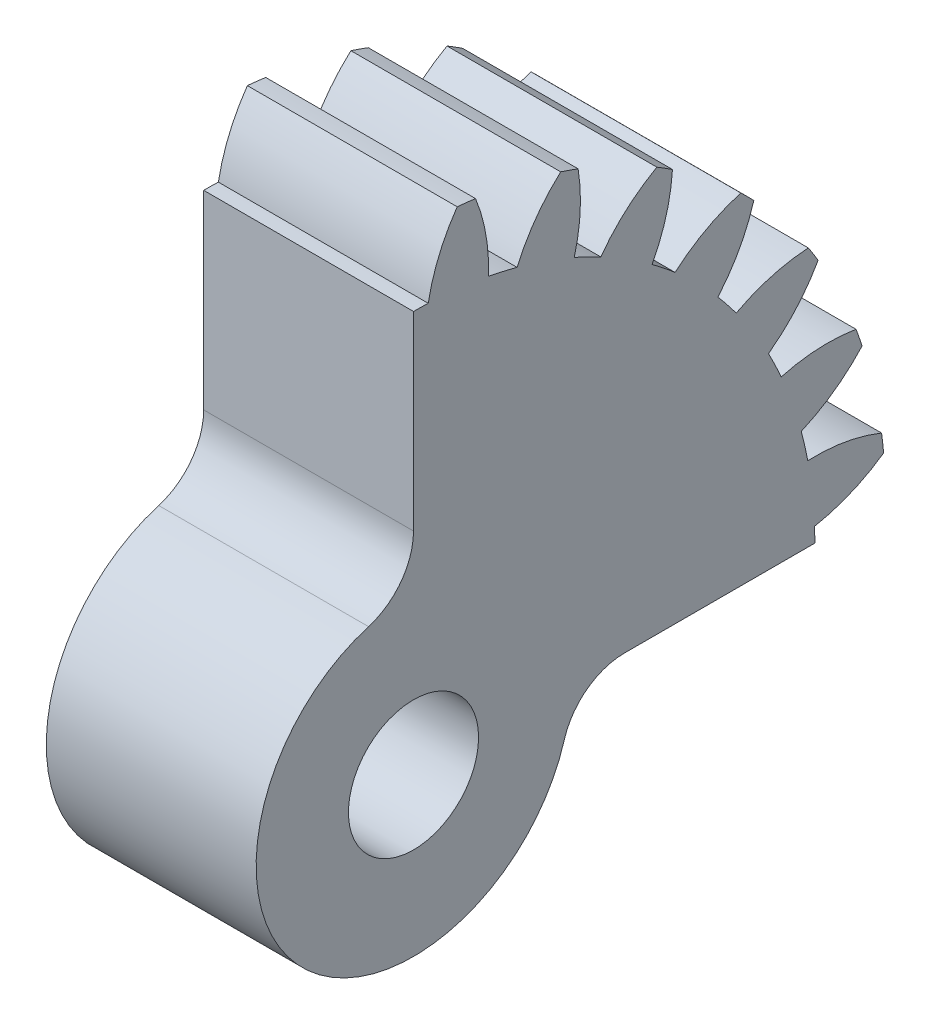
SolidWorks part; units mm, degrees
ref_plane "Plane1" through (0, 0, 0) normal (0, 0, 1) x (1, 0, 0)
ref_plane "Plane2" through (0, 0, 0) normal (0, 1, 0) x (1, 0, 0)
ref_plane "Plane3" through (0, 0, 0) normal (1, 0, 0) x (0, 0, -1)
sketch "HoldingSke" plane through (0, 0, 0) normal (0, 1, 0) x (1, 0, 0)
  line L0 (0, 0) -> (0.5886, -0.313)
  line L1 (-15, 0) -> (100, 0) construction
  line L2 (0, 0) -> (-2.1039, 2.3779)
  line L3 (0, 0) -> (-11.863, 4.5341)
  line L4 (0, 0) -> (7.6251, 4.0544)
  line L5 (0, 0) -> (-46.8476, -17.4728)
  line L6 (0, 0) -> (-8.2896, -5.593)
  line L7 (-2.1039, 2.3779) -> (8.6586, 51.2059)
  line L8 (-76.2, 54.61) -> (-73.9, 54.61)
  line L9 (-71.009, 38.7566) -> (-53.1078, 45.2721)
  line L10 (-76.2, 71.12) -> (104.1128, 71.12)
  line L11 (0, 0) -> (-10, 0)
  line L12 (-76.2, 101.6) -> (-76.147, 101.6)
  line L13 (24.9733, 27.94) -> (52.9518, 28.4284)
  line L14 (24.9733, 27.94) -> (24.9743, 27.94)
  line L15 (24.9733, 27.94) -> (100.4006, 29.5858)
  line L16 (-63.627, -1.5) -> (-12.827, -1.5)
  circle A0 centre (0, 0) radius 7.5
  circle A1 centre (0, 0) radius 19.124
  circle A2 centre (0, 0) radius 37.5
  circle A3 centre (0, 0) radius 7.5
  dimension "MHD" = 38.248
  dimension "Hub_dia" = 75
  dimension "Bore" = 15
  dimension "MBD" = 15
  dimension "Num_teeth" = 28
  dimension "Pitch_radius" = 180.3128
  dimension "Pitch" = 0.6667
  dimension "Width" = 10
  dimension "Overall_len" = 50
  dimension "Show_teeth" = 28
  dimension "Thickness" = 10
  dimension "OAL" = 50.0001
  dimension "T_dim" = 2.3
  dimension "Ap" = 20
  dimension "H" = 19.05
  dimension "Backlash" = 0.053
  dimension "Addendum_fac" = 1
  dimension "Dedendum_fac" = 1.25
  dimension "Clearance_fac" = 0.25
  dimension "Dedendum_add" = 0.001
  dimension "Module" = 1.5
sketch "BasProSke" plane through (0, 0, 0) normal (0, 1, 0) x (1, 0, 0)
  line L0 (-10, 0) -> (60, 0) construction
  line L1 (0, 0) -> (0, 22.5)
  line L2 (0, 0) -> (10, 0)
  line L3 (10, 0) -> (10, 22.5)
  line L4 (10, 22.5) -> (0, 22.5)
  dimension "Diameter" = 45
  dimension "Thickness" = 10
revolve "Base-Revolve" add sketch "BasProSke" angle 360 about L0
sketch "TooCutSke" plane through (0, 0, 0) normal (1, 0, 0) x (0, 0, -1)
  line L1 (0, 0) -> (0, 107) construction
  line L2 (0, 0) -> (-1.2702, 20.9615) construction
  line L3 (0, 0) -> (-4.6962, 41.6802) construction
  line L4 (-1.2702, 20.9615) -> (-2.3481, 20.8401) construction
  arc A0 (0.7007, 19.1112) -> (-0.7007, 19.1112) centre (0, 0) ccw
  arc A1 (2.0988, 22.4274) -> (-2.0988, 22.4274) centre (0, 0) ccw
  circle A2 centre (0, 0) radius 21 construction
  circle A3 centre (0, 0) radius 19.7335 construction
  arc A4 (-0.7007, 19.1112) -> (-2.0988, 22.4274) centre (-8.9603, 17.5819) ccw
  arc A5 (2.0988, 22.4274) -> (0.7007, 19.1112) centre (8.9603, 17.5819) ccw
  dimension "Root_dia" = 38.248
  dimension "Overcut_dia" = 45.0508
  dimension "Pitch_dia" = 42
  dimension "Base_dia" = 39.4671
  dimension "Flank_rad" = 8.4
  dimension "Half_ang" = 6.429
  dimension "Half_CT" = 1.0847
extrude "ToothCut" cut sketch "TooCutSke" along normal through all
fillet "Breaks" [suppressed] radius 0.03
fillet "RootFillets" [suppressed] radius 0.376
pattern_circular "TeethCuts" count 28 every 12.857 about axis through (-10, 0, 0) along (1, 0, 0) of "ToothCut", "RootFillets", "Breaks"
sketch "HubNeaOneSke" plane through (0, 0, 0) normal (-1, 0, 0) x (0, 0, 1)
  circle A0 centre (0, 0) radius 19.124
  dimension "Diameter" = 38.248
extrude "HubNearOne" [suppressed] add sketch "HubNeaOneSke" along normal blind 40.0001
sketch "HubNeaBotSke" plane through (0, 0, 0) normal (-1, 0, 0) x (0, 0, 1)
  circle A0 centre (0, 0) radius 19.124
  dimension "Diameter" = 38.248
extrude "HubNearBoth" [suppressed] add sketch "HubNeaBotSke" along normal blind 20
ref_plane "FarPln" through (10, 0, 0) normal (1, 0, 0) x (0, 0, -1)
sketch "HubFarSke" plane through (10, 0, 0) normal (1, 0, 0) x (0, 0, -1)
  circle A0 centre (0, 0) radius 19.124
  dimension "Diameter" = 38.248
extrude "HubFar" [suppressed] add sketch "HubFarSke" along normal blind 20
sketch "BorSke" plane through (0, 0, 0) normal (1, 0, 0) x (0, 0, -1)
  circle A0 centre (0, 0) radius 7.5
  dimension "Diameter" = 15
extrude "Bore" cut sketch "BorSke" along normal mid plane 100.0001
sketch "KeySke" plane through (0, 0, 0) normal (1, 0, 0) x (0, 0, -1)
  line L0 (-2.5, 0) -> (-2.5, 9.8)
  line L1 (-2.5, 9.8) -> (2.5, 9.8)
  line L2 (2.5, 9.8) -> (2.5, 0)
  line L3 (0, 0) -> (0, 34) construction
  line L4 (-2.5, 0) -> (2.5, 0)
  dimension "Offset" = 9.8
  dimension "Width" = 5
extrude "Keyway" [suppressed] cut sketch "KeySke" along normal mid plane 100.0001
pattern_circular "Keyway2" [suppressed] count 2 every 90 about axis through (-10, 0, 0) along (1, 0, 0)
sketch "Croquis1" plane through (10, 0, 0) normal (1, 0, 0) x (0, 0, -1)
  line L0 (0, 19.124) -> (0, 0)
  line L1 (0, 0) -> (19.124, 0)
  arc A0 (0.7007, 19.1112) -> (-0.7007, 19.1112) centre (0, 0) ccw construction
  arc A1 (19.1112, -0.7007) -> (19.1112, 0.7007) centre (0, 0) ccw construction
  arc A2 (0, 19.124) -> (19.124, 0) centre (16.9551, 16.9551) cw
extrude "Extruir1" cut sketch "Croquis1" against normal blind 10 flip side to cut
sketch "Croquis2" plane through (10, 0, 0) normal (1, 0, 0) x (0, 0, -1)
  circle A0 centre (0, 0) radius 7.5
  circle A1 centre (0, 0) radius 3.1
  dimension "D1" = 6.2
extrude "Extruir2" add sketch "Croquis2" against normal through all
fillet "Redondeo1" radius 3 2 edges at (5, 7.5, 0) (5, 0, -7.5)
equation "' \"Module@HoldingSke\" = 6.35"
equation "' \"Num_teeth@HoldingSke\" = 12"
equation "' \"Ap@HoldingSke\" =  20"
equation "' \"Width@HoldingSke\" = 0.5 * 25.4"
equation "' \"Hub_dia@HoldingSke\"= 1 * 25.4"
equation "' \"Overall_len@HoldingSke\" = 1.0 * 25.4"
equation "' \"Bore@HoldingSke\" = 0.75 * 25.4"
equation "' \"T_dim@HoldingSke\" = 0.1 * 25.4"
equation "' \"Width@KeySke\" = 0.25 * 25.4"
equation "' \"Show_teeth@HoldingSke\" = 13"
equation "' \"Backlash@HoldingSke\" = 0.009 * 25.4"
equation "' \"Addendum_fac@HoldingSke\" = 1.0"
equation "' \"Dedendum_fac@HoldingSke\" = 1.25"
equation "' \"Dedendum_add@HoldingSke\" = 0.00005 * 25.4"
equation "' \"Clearance_fac@HoldingSke\" = 0.25"
equation "\"Pitch@HoldingSke\" = 1 / \"Module@HoldingSke\""
equation "\"Overcut_dia@TooCutSke\" = (\"Num_teeth@HoldingSke\" + 2 * \"Addendum_fac@HoldingSke\") / \"Pitch@HoldingSke\" + 0.002 * 25.4"
equation "\"Pitch_dia@TooCutSke\" = \"Num_teeth@HoldingSke\" / \"Pitch@HoldingSke\""
equation "\"Base_dia@TooCutSke\" = \"Num_teeth@HoldingSke\" / \"Pitch@HoldingSke\" * cos((\"Ap@HoldingSke\"  * 3.14159265 / 180))"
equation "\"Root_dia@TooCutSke\" = (\"Num_teeth@HoldingSke\" + 2) / \"Pitch@HoldingSke\" - 2 * (\"Addendum_fac@HoldingSke\" + \"Dedendum_fac@HoldingSke\") / \"Pitch@HoldingSke\" - \"Dedendum_add@HoldingSke\" * 2"
equation "\"Half_ang@TooCutSke\" = 180 / \"Num_teeth@HoldingSke\""
equation "\"Half_CT@TooCutSke\" = \"Num_teeth@HoldingSke\" / \"Pitch@HoldingSke\" * sin((3.14159265 / 2 / \"Num_teeth@HoldingSke\")) / 2 - 7 * \"Backlash@HoldingSke\" / 4"
equation "\"Flank_rad@TooCutSke\" = \"Num_teeth@HoldingSke\" / \"Pitch@HoldingSke\" / 5"
equation "\"Radius@RootFillets\" = \"Clearance_fac@HoldingSke\" / \"Pitch@HoldingSke\" + \"Dedendum_add@HoldingSke\""
equation "\"Break_rad@Breaks\" = 0.02 / \"Pitch@HoldingSke\""
equation "\"Thickness@HoldingSke\" = \"Width@HoldingSke\""
equation "\"OAL@HoldingSke\" = \"Thickness@HoldingSke\""
equation "\"MHD@HoldingSke\" = (\"Num_teeth@HoldingSke\" + 2) / \"Pitch@HoldingSke\" - 2 * (\"Addendum_fac@HoldingSke\" + \"Dedendum_fac@HoldingSke\")  / \"Pitch@HoldingSke\" - \"Dedendum_add@HoldingSke\" * 2"
equation "\"MBD@HoldingSke\" = (\"Num_teeth@HoldingSke\" + 2) / \"Pitch@HoldingSke\" - 2 * (\"Addendum_fac@HoldingSke\" + \"Dedendum_fac@HoldingSke\")  / \"Pitch@HoldingSke\" - \"Dedendum_add@HoldingSke\" * 2 - 0.002 * 25.4"
equation "\"MHD@HoldingSke\" = ((sgn( \"MHD@HoldingSke\" - \"Hub_dia@HoldingSke\" )-1)*( \"MHD@HoldingSke\" - \"Hub_dia@HoldingSke\" ))/-2+ \"Hub_dia@HoldingSke\""
equation "\"MBD@HoldingSke\" = ((sgn( \"MBD@HoldingSke\" - \"Bore@HoldingSke\" )-1)*( \"MBD@HoldingSke\" - \"Bore@HoldingSke\" ))/-2+ \"Bore@HoldingSke\""
equation "\"OAL@HoldingSke\" = ((sgn( \"OAL@HoldingSke\" - \"Overall_len@HoldingSke\" )+1)*( \"OAL@HoldingSke\" - \"Overall_len@HoldingSke\" ))/2 + \"Overall_len@HoldingSke\" + 0.000002 * 25.4"
equation "\"Num_teeth@TeethCuts\" = int( \"Show_teeth@HoldingSke\" ) + 1"
equation "\"Num_teeth@TeethCuts\" = ((sgn( \"Num_teeth@TeethCuts\" - \"Num_teeth@HoldingSke\" )-1)*( \"Num_teeth@TeethCuts\" - \"Num_teeth@HoldingSke\" ))/-2+ \"Num_teeth@HoldingSke\""
equation "\"Num_teeth@TeethCuts\" = ((sgn( \"Num_teeth@TeethCuts\" - 2.0)+1)*( \"Num_teeth@TeethCuts\" - 2.0))/2 +2.0"
equation "\"Angle@TeethCuts\" = 360.0 / \"Num_teeth@HoldingSke\""
equation "\"Diameter@BasProSke\" = (\"Num_teeth@HoldingSke\" + 2 * \"Addendum_fac@HoldingSke\") / \"Pitch@HoldingSke\""
equation "\"Thickness@BasProSke\"  = \"Thickness@HoldingSke\""
equation "' \"Fillet_rad@BasProSke\" =  \"Thickness@HoldingSke\" * 0.05"
equation "\"MHD@HoldingSke\" = ((sgn( \"MHD@HoldingSke\" - \"Root_dia@TooCutSke\" )-1)*( \"MHD@HoldingSke\" - \"Root_dia@TooCutSke\" ))/-2+ \"Root_dia@TooCutSke\""
equation "\"Diameter@HubNeaOneSke\" = \"MHD@HoldingSke\""
equation "\"Length@HubNearOne\" = \"OAL@HoldingSke\" - \"Thickness@BasProSke\""
equation "\"Diameter@HubNeaBotSke\" = \"MHD@HoldingSke\""
equation "\"Length@HubNearBoth\" = ( \"OAL@HoldingSke\" - \"Thickness@BasProSke\" ) / 2.0"
equation "\"Thickness@FarPln\" = \"Thickness@BasProSke\""
equation "\"Diameter@HubFarSke\" = \"MHD@HoldingSke\""
equation "\"Length@HubFar\" = ( \"OAL@HoldingSke\" - \"Thickness@BasProSke\" ) / 2.0"
equation "\"Diameter@BorSke\" = \"MBD@HoldingSke\""
equation "\"D1@Bore\" = \"OAL@HoldingSke\" * 2.0"
equation "\"D1@Keyway\" = \"OAL@HoldingSke\" * 2.0"
equation "\"Offset@KeySke\" = \"T_dim@HoldingSke\" + \"MBD@HoldingSke\" / 2.0"
